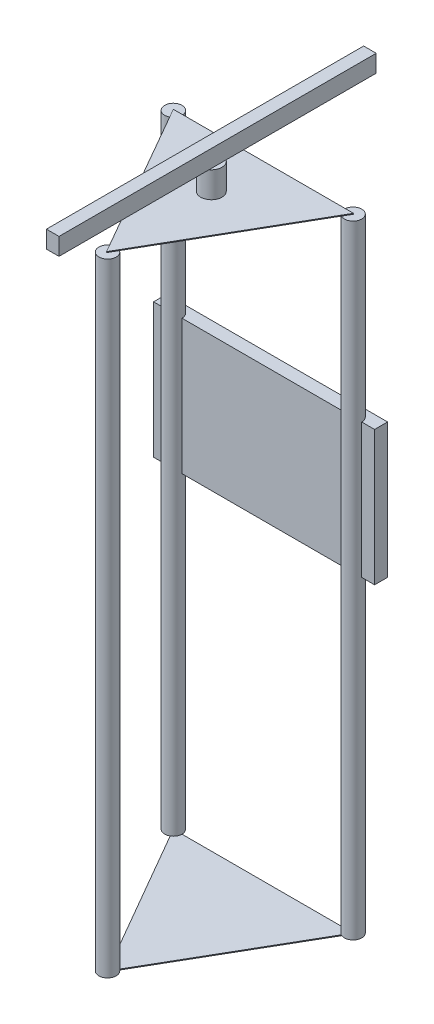
SolidWorks part; units mm, degrees
ref_plane "Front Plane" through (0, 0, 0) normal (0, 0, 1) x (1, 0, 0)
ref_plane "Top Plane" through (0, 0, 0) normal (0, 1, 0) x (1, 0, 0)
ref_plane "Right Plane" through (0, 0, 0) normal (1, 0, 0) x (0, 0, -1)
sketch "Sketch1" plane through (0, 0, 0) normal (0, 1, 0) x (1, 0, 0)
  line L1 (0, -304.8) -> (263.9645, 152.4)
  line L2 (263.9645, 152.4) -> (-263.9645, 152.4)
  line L3 (-263.9645, 152.4) -> (0, -304.8)
  circle A0 centre (0, 0) radius 152.4 construction
extrude "Boss-Extrude1" add sketch "Sketch1" along normal blind 2.54
sketch "Sketch2" plane through (0, 2.54, 0) normal (0, 1, 0) x (1, 0, 0)
  circle A0 centre (0, -304.8) radius 25.4
  circle A1 centre (-263.9645, 152.4) radius 25.4
  circle A2 centre (263.9645, 152.4) radius 25.4
extrude "Boss-Extrude2" add sketch "Sketch2" along normal blind 1828.8 contours A1 | A0 | A2
sketch "Sketch3" plane through (0, 1831.34, 0) normal (0, 1, 0) x (1, 0, 0)
  line L0 (-263.9645, 152.4) -> (0, -307.726)
  line L1 (0, -307.726) -> (265.0592, 152.4)
  line L2 (265.0592, 152.4) -> (-263.9645, 152.4)
  circle M4 centre (-263.9645, 152.4) radius 25.4
extrude "Boss-Extrude3" add sketch "Sketch3" along normal blind 2.54 contours L1 L2 L0 M4
sketch "Sketch4" plane through (0, 1833.88, 0) normal (0, 1, 0) x (1, 0, 0)
  circle A0 centre (0, 0) radius 31.1098
extrude "Boss-Extrude5" add sketch "Sketch4" along normal blind 76.2 contours A0
sketch "Sketch5" plane through (0, 1910.08, 0) normal (0, 1, 0) x (1, 0, 0)
  line L1 (18.4507, -465.9087) -> (-18.4507, -465.9087)
  line L2 (18.4507, -465.9087) -> (18.4507, 465.9087)
  line L3 (18.4507, 465.9087) -> (-18.4507, 465.9087)
  line L4 (-18.4507, -465.9087) -> (-18.4507, 465.9087)
  line L5 (18.4507, -465.9087) -> (-18.4507, 465.9087) construction
  line L6 (18.4507, 465.9087) -> (-18.4507, -465.9087) construction
  point P0 (0, 0)
extrude "Boss-Extrude7" add sketch "Sketch5" along normal blind 50.8
sketch3d "3DSketch1"
  line L0 (238.5645, 2.54, -152.4) -> (-238.5645, 2.54, -152.4) construction
  line L1 (265.0592, 1833.88, -152.4) -> (-263.9645, 1833.88, -152.4) construction
  line L3 (327.2548, 1315.1145, -152.4) -> (-322.0326, 1315.1145, -152.4)
  line L4 (327.2548, 1315.1145, -152.4) -> (327.2548, 919.7383, -152.4)
  line L5 (327.2548, 919.7383, -152.4) -> (-322.0326, 919.7383, -152.4)
  line L6 (-322.0326, 1315.1145, -152.4) -> (-322.0326, 919.7383, -152.4)
  line L7 (327.2548, 1315.1145, -152.4) -> (-322.0326, 919.7383, -152.4) construction
  line L8 (327.2548, 919.7383, -152.4) -> (-322.0326, 1315.1145, -152.4) construction
  point P4 (2.6111, 1117.4264, -152.4)
extrude "Boss-Extrude8" add sketch "3DSketch1" along direction (0, 0, 1) on the side against the normal blind 38.1
